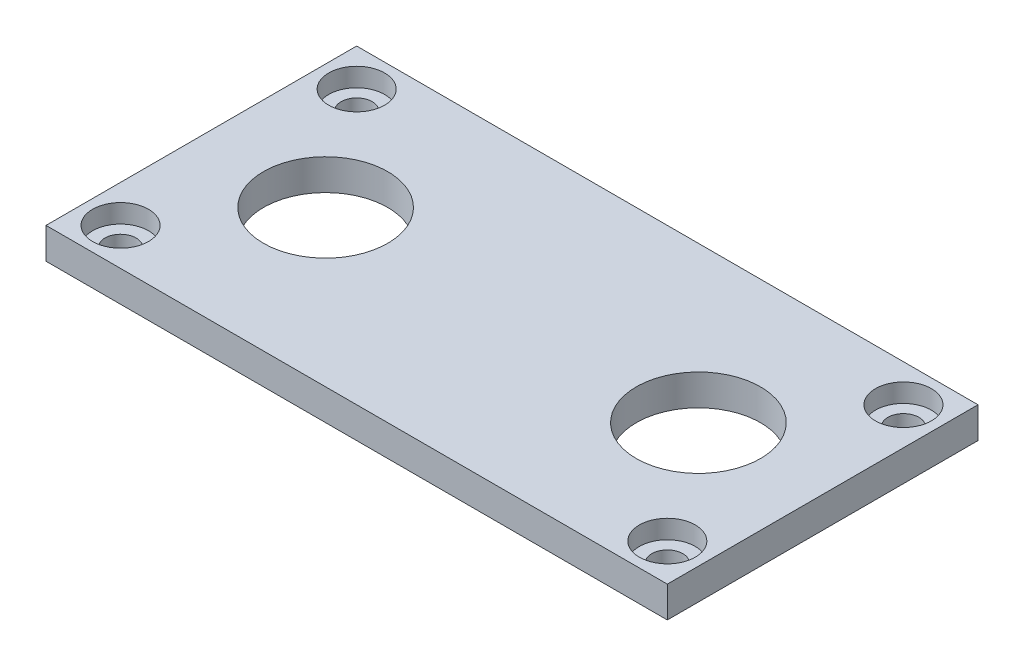
SolidWorks part; units mm, degrees
ref_plane "Ön Düzlem" through (0, 0, 0) normal (0, 0, 1) x (1, 0, 0)
ref_plane "Üst Düzlem" through (0, 0, 0) normal (0, 1, 0) x (1, 0, 0)
ref_plane "Sağ Düzlem" through (0, 0, 0) normal (1, 0, 0) x (0, 0, -1)
sketch "Sketch1" plane through (0, 0, 0) normal (0, 1, 0) x (1, 0, 0)
  line L1 (-50, -25) -> (50, -25)
  line L2 (-50, -25) -> (-50, 25)
  line L3 (-50, 25) -> (50, 25)
  line L4 (50, -25) -> (50, 25)
  circle A0 centre (30, 0) radius 10
  circle A1 centre (-30, 0) radius 10
  circle A2 centre (44, 19) radius 2.5
  circle A3 centre (-44, 19) radius 2.5
  circle A4 centre (-44, -19) radius 2.5
  circle A5 centre (44, -19) radius 2.5
  dimension "D5" = 20
  dimension "D6" = 20
  dimension "D7" = 5
  dimension "D1" = 100
  dimension "D2" = 50
  dimension "D3" = 50
  dimension "D4" = 25
  dimension "D8" = 6
  dimension "D9" = 6
  dimension "D10" = 6
  dimension "D11" = 6
  dimension "D12" = 20
  dimension "D13" = 20
extrude "Boss-Extrude1" add sketch "Sketch1" along normal blind 5
sketch "Sketch2" plane through (0, 5, 0) normal (0, 1, 0) x (1, 0, 0)
  circle A0 centre (-44, 19) radius 4.5
  circle A1 centre (-44, -19) radius 4.5
  circle A2 centre (44, -19) radius 4.5
  circle A3 centre (44, 19) radius 4.5
  dimension "D1" = 9
extrude "Cut-Extrude1" cut sketch "Sketch2" against normal blind 3
